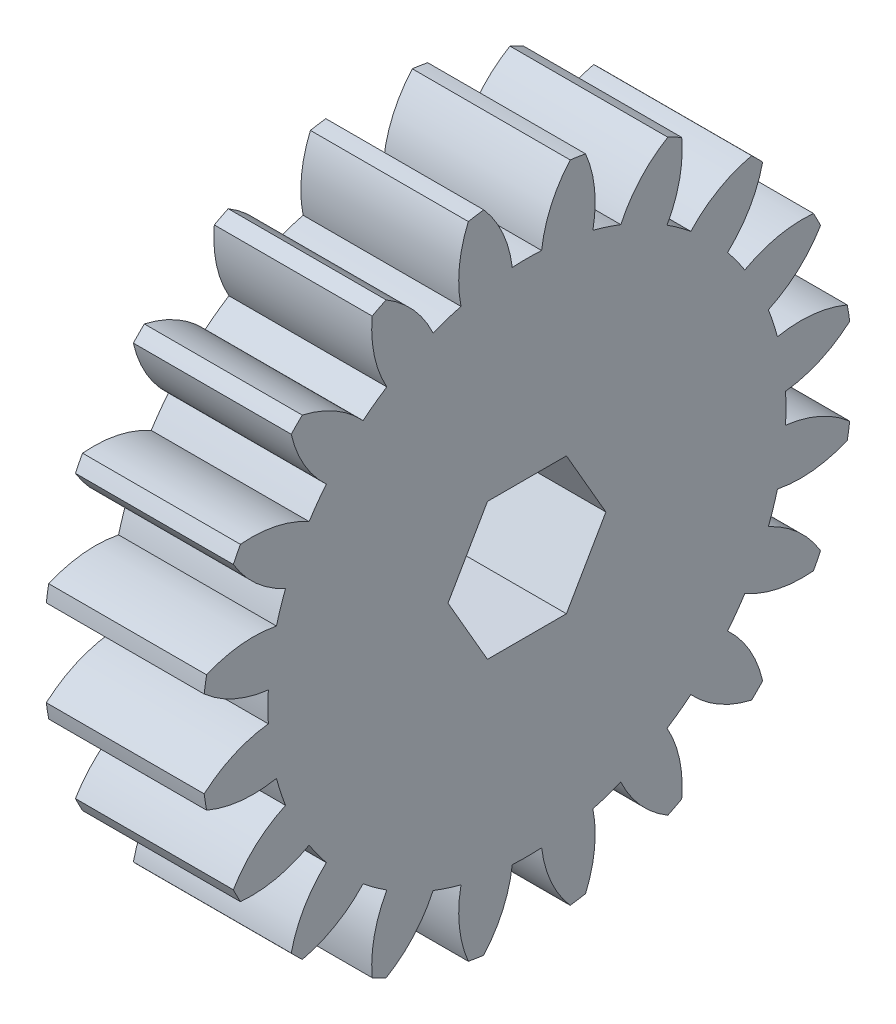
SolidWorks part; units mm, degrees
ref_plane "Plane1" through (0, 0, 0) normal (0, 0, 1) x (1, 0, 0)
ref_plane "Plane2" through (0, 0, 0) normal (0, 1, 0) x (1, 0, 0)
ref_plane "Plane3" through (0, 0, 0) normal (1, 0, 0) x (0, 0, -1)
sketch "HoldingSke" plane through (0, 0, 0) normal (0, 1, 0) x (1, 0, 0)
  line L0 (0, 0) -> (0.6265, -0.228)
  line L1 (-15, 0) -> (100, 0) construction
  line L2 (0, 0) -> (-2.1039, 2.3779)
  line L3 (0, 0) -> (-11.863, 4.5341)
  line L4 (0, 0) -> (8.1152, 2.9537)
  line L5 (0, 0) -> (-46.8476, -17.4728)
  line L6 (0, 0) -> (-9.9476, -6.7116)
  line L7 (-2.1039, 2.3779) -> (8.6586, 51.2059)
  line L8 (-76.2, 54.61) -> (-75.3, 54.61)
  line L9 (-71.009, 38.7566) -> (-53.1078, 45.2721)
  line L10 (-76.2, 71.12) -> (104.1128, 71.12)
  line L11 (0, 0) -> (-12, 0)
  line L12 (-76.2, 101.6) -> (-76.147, 101.6)
  line L13 (24.9733, 27.94) -> (52.9518, 28.4284)
  line L14 (24.9733, 27.94) -> (24.9743, 27.94)
  line L15 (24.9733, 27.94) -> (100.4006, 29.5858)
  line L16 (-63.627, -1.5) -> (-12.827, -1.5)
  circle A0 centre (0, 0) radius 2.5
  circle A1 centre (0, 0) radius 13.124
  circle A2 centre (0, 0) radius 37.5
  circle A3 centre (0, 0) radius 2.5
  dimension "MHD" = 26.248
  dimension "Hub_dia" = 75
  dimension "Bore" = 5
  dimension "MBD" = 5
  dimension "Num_teeth" = 20
  dimension "Pitch" = 0.6667
  dimension "Overall_len" = 50
  dimension "Show_teeth" = 20
  dimension "Thickness" = 12
  dimension "OAL" = 50.0001
  dimension "T_dim" = 0.9
  dimension "Ap" = 20
  dimension "H" = 19.05
  dimension "Pitch_radius" = 180.3128
  dimension "Width" = 12
  dimension "Backlash" = 0.053
  dimension "Addendum_fac" = 1
  dimension "Dedendum_fac" = 1.25
  dimension "Clearance_fac" = 0.25
  dimension "Dedendum_add" = 0.001
  dimension "Module" = 1.5
sketch "BasProSke" plane through (0, 0, 0) normal (0, 1, 0) x (1, 0, 0)
  line L0 (-10, 0) -> (60, 0) construction
  line L1 (0, 0) -> (0, 16.5)
  line L2 (0, 0) -> (8, 0)
  line L3 (8, 0) -> (8, 16.5)
  line L4 (8, 16.5) -> (0, 16.5)
  dimension "Thickness" = 8
  dimension "Diameter" = 33
revolve "Base-Revolve" add sketch "BasProSke" angle 360 about L0
sketch "TooCutSke" plane through (0, 0, 0) normal (1, 0, 0) x (0, 0, -1)
  line L1 (0, 0) -> (0, 107) construction
  line L2 (0, 0) -> (-1.2696, 14.9462) construction
  line L3 (0, 0) -> (-4.6808, 29.5532) construction
  line L4 (-1.2696, 14.9462) -> (-2.3404, 14.7766) construction
  arc A0 (0.7438, 13.1029) -> (-0.7438, 13.1029) centre (0, 0) ccw
  arc A1 (2.21, 16.377) -> (-2.21, 16.377) centre (0, 0) ccw
  circle A2 centre (0, 0) radius 15 construction
  circle A3 centre (0, 0) radius 14.0954 construction
  arc A4 (-0.7438, 13.1029) -> (-2.21, 16.377) centre (-6.7025, 12.3999) ccw
  arc A5 (2.21, 16.377) -> (0.7438, 13.1029) centre (6.7025, 12.3999) ccw
  dimension "Root_dia" = 26.248
  dimension "Overcut_dia" = 33.0508
  dimension "Pitch_dia" = 30
  dimension "Base_dia" = 28.1908
  dimension "Flank_rad" = 6
  dimension "Half_ang" = 9
  dimension "Half_CT" = 1.0841
extrude "ToothCut" cut sketch "TooCutSke" along normal through all
fillet "Breaks" [suppressed] radius 0.03
fillet "RootFillets" [suppressed] radius 0.376
pattern_circular "TeethCuts" count 20 every 18 about axis through (-10, 0, 0) along (1, 0, 0) of "ToothCut", "RootFillets", "Breaks"
sketch "HubNeaOneSke" plane through (0, 0, 0) normal (-1, 0, 0) x (0, 0, 1)
  circle A0 centre (0, 0) radius 13.124
  dimension "Diameter" = 26.248
extrude "HubNearOne" [suppressed] add sketch "HubNeaOneSke" along normal blind 42.0001
sketch "HubNeaBotSke" plane through (0, 0, 0) normal (-1, 0, 0) x (0, 0, 1)
  circle A0 centre (0, 0) radius 13.124
  dimension "Diameter" = 26.248
extrude "HubNearBoth" [suppressed] add sketch "HubNeaBotSke" along normal blind 21
ref_plane "FarPln" through (8, 0, 0) normal (1, 0, 0) x (0, 0, -1)
sketch "HubFarSke" plane through (8, 0, 0) normal (1, 0, 0) x (0, 0, -1)
  circle A0 centre (0, 0) radius 13.124
  dimension "Diameter" = 26.248
extrude "HubFar" [suppressed] add sketch "HubFarSke" along normal blind 21
sketch "BorSke" plane through (0, 0, 0) normal (1, 0, 0) x (0, 0, -1)
  circle A0 centre (0, 0) radius 2.5
  dimension "Diameter" = 5
extrude "Bore" cut sketch "BorSke" along normal mid plane 100.0001
sketch "KeySke" plane through (0, 0, 0) normal (1, 0, 0) x (0, 0, -1)
  line L0 (-1, 0) -> (-1, 3.4)
  line L1 (-1, 3.4) -> (1, 3.4)
  line L2 (1, 3.4) -> (1, 0)
  line L3 (0, 0) -> (0, 34) construction
  line L4 (-1, 0) -> (1, 0)
  dimension "Offset" = 3.4
  dimension "Width" = 2
extrude "Keyway" [suppressed] cut sketch "KeySke" along normal mid plane 100.0001
pattern_circular "Keyway2" [suppressed] count 2 every 90 about axis through (-10, 0, 0) along (1, 0, 0)
sketch "Sketch1" plane through (8, 0, 0) normal (1, 0, 0) x (0, 0, -1)
  line L1 (4, 0) -> (2, 3.4641)
  line L2 (2, 3.4641) -> (-2, 3.4641)
  line L3 (-2, 3.4641) -> (-4, 0)
  line L4 (-4, 0) -> (-2, -3.4641)
  line L5 (-2, -3.4641) -> (2, -3.4641)
  line L6 (2, -3.4641) -> (4, 0)
  circle A0 centre (0, 0) radius 3.4641 construction
  circle A1 centre (0, 0) radius 4 construction
  dimension "D1" = 8
extrude "Cut-Extrude1" cut sketch "Sketch1" against normal through all
ref_plane "Plane4" through (8, 16.2303, -2.9711) normal (1, 0, 0) x (0, 0, -1)
sketch "Sketch2" plane through (8, 16.2303, -2.9711) normal (1, 0, 0) x (0, 0, -1)
  line L0 (-6.9711, -16.2303) -> (-4.9711, -19.6944) construction
  line L1 (-4.9711, -19.6944) -> (-0.9711, -19.6944) construction
  line L2 (-0.9711, -19.6944) -> (1.0289, -16.2303) construction
  line L3 (1.0289, -16.2303) -> (-0.9711, -12.7662) construction
  line L4 (-0.9711, -12.7662) -> (-4.9711, -12.7662) construction
  line L5 (-4.9711, -12.7662) -> (-6.9711, -16.2303) construction
  line L6 (-4.9711, -12.7662) -> (-6.9711, -16.2303)
  line L7 (-0.9711, -12.7662) -> (-4.9711, -12.7662)
  line L8 (1.0289, -16.2303) -> (-0.9711, -12.7662)
  line L9 (-0.9711, -19.6944) -> (1.0289, -16.2303)
  line L10 (-4.9711, -19.6944) -> (-0.9711, -19.6944)
  line L11 (-6.9711, -16.2303) -> (-4.9711, -19.6944)
  circle A0 centre (-2.9711, -16.2303) radius 7.5
  dimension "D1" = 15
extrude "Boss-Extrude1" [suppressed] add sketch "Sketch2" along normal blind 2.5
sketch "Sketch3" plane through (0, 0, 0) normal (-1, 0, 0) x (0, 0, 1)
  line L0 (2, 3.4641) -> (4, 0) construction
  line L1 (-2, 3.4641) -> (2, 3.4641) construction
  line L2 (-4, 0) -> (-2, 3.4641) construction
  line L3 (-2, -3.4641) -> (-4, 0) construction
  line L4 (2, -3.4641) -> (-2, -3.4641) construction
  line L5 (4, 0) -> (2, -3.4641) construction
  line L6 (4, 0) -> (2, -3.4641)
  line L7 (2, -3.4641) -> (-2, -3.4641)
  line L8 (-2, -3.4641) -> (-4, 0)
  line L9 (-4, 0) -> (-2, 3.4641)
  line L10 (-2, 3.4641) -> (2, 3.4641)
  line L11 (2, 3.4641) -> (4, 0)
  circle A0 centre (0, 0) radius 7.5
  dimension "D1" = 15
extrude "Boss-Extrude2" [suppressed] add sketch "Sketch3" along normal blind 2.5
equation "' \"Module@HoldingSke\" = 6.35"
equation "' \"Num_teeth@HoldingSke\" = 12"
equation "' \"Ap@HoldingSke\" =  20"
equation "' \"Ap@HoldingSke\" = 20"
equation "' \"Width@HoldingSke\" = 0.5 * 25.4"
equation "' \"Hub_dia@HoldingSke\"= 1 * 25.4"
equation "' \"Hub_dia@HoldingSke\" = 1 * 25.4"
equation "' \"Overall_len@HoldingSke\" = 1.0 * 25.4"
equation "' \"Bore@HoldingSke\" = 0.75 * 25.4"
equation "' \"T_dim@HoldingSke\" = 0.1 * 25.4"
equation "' \"Width@KeySke\" = 0.25 * 25.4"
equation "' \"Show_teeth@HoldingSke\" = 13"
equation "' \"Backlash@HoldingSke\" = 0.009 * 25.4"
equation "' \"Addendum_fac@HoldingSke\" = 1.0"
equation "' \"Dedendum_fac@HoldingSke\" = 1.25"
equation "' \"Dedendum_add@HoldingSke\" = 0.00005 * 25.4"
equation "' \"Clearance_fac@HoldingSke\" = 0.25"
equation "\"Pitch@HoldingSke\" = 1 / \"Module@HoldingSke\""
equation "\"Overcut_dia@TooCutSke\" = (\"Num_teeth@HoldingSke\" + 2 * \"Addendum_fac@HoldingSke\") / \"Pitch@HoldingSke\" + 0.002 * 25.4"
equation "\"Pitch_dia@TooCutSke\" = \"Num_teeth@HoldingSke\" / \"Pitch@HoldingSke\""
equation "\"Base_dia@TooCutSke\" = \"Num_teeth@HoldingSke\" / \"Pitch@HoldingSke\" * cos((\"Ap@HoldingSke\"  * 3.14159265 / 180))"
equation "\"Root_dia@TooCutSke\" = (\"Num_teeth@HoldingSke\" + 2) / \"Pitch@HoldingSke\" - 2 * (\"Addendum_fac@HoldingSke\" + \"Dedendum_fac@HoldingSke\") / \"Pitch@HoldingSke\" - \"Dedendum_add@HoldingSke\" * 2"
equation "\"Half_ang@TooCutSke\" = 180 / \"Num_teeth@HoldingSke\""
equation "\"Half_CT@TooCutSke\" = \"Num_teeth@HoldingSke\" / \"Pitch@HoldingSke\" * sin((3.14159265 / 2 / \"Num_teeth@HoldingSke\")) / 2 - 7 * \"Backlash@HoldingSke\" / 4"
equation "\"Flank_rad@TooCutSke\" = \"Num_teeth@HoldingSke\" / \"Pitch@HoldingSke\" / 5"
equation "\"Radius@RootFillets\" = \"Clearance_fac@HoldingSke\" / \"Pitch@HoldingSke\" + \"Dedendum_add@HoldingSke\""
equation "\"Break_rad@Breaks\" = 0.02 / \"Pitch@HoldingSke\""
equation "\"Thickness@HoldingSke\" = \"Width@HoldingSke\""
equation "\"OAL@HoldingSke\" = \"Thickness@HoldingSke\""
equation "\"MHD@HoldingSke\" = (\"Num_teeth@HoldingSke\" + 2) / \"Pitch@HoldingSke\" - 2 * (\"Addendum_fac@HoldingSke\" + \"Dedendum_fac@HoldingSke\")  / \"Pitch@HoldingSke\" - \"Dedendum_add@HoldingSke\" * 2"
equation "\"MBD@HoldingSke\" = (\"Num_teeth@HoldingSke\" + 2) / \"Pitch@HoldingSke\" - 2 * (\"Addendum_fac@HoldingSke\" + \"Dedendum_fac@HoldingSke\")  / \"Pitch@HoldingSke\" - \"Dedendum_add@HoldingSke\" * 2 - 0.002 * 25.4"
equation "\"MHD@HoldingSke\" = ((sgn( \"MHD@HoldingSke\" - \"Hub_dia@HoldingSke\" )-1)*( \"MHD@HoldingSke\" - \"Hub_dia@HoldingSke\" ))/-2+ \"Hub_dia@HoldingSke\""
equation "\"MBD@HoldingSke\" = ((sgn( \"MBD@HoldingSke\" - \"Bore@HoldingSke\" )-1)*( \"MBD@HoldingSke\" - \"Bore@HoldingSke\" ))/-2+ \"Bore@HoldingSke\""
equation "\"OAL@HoldingSke\" = ((sgn( \"OAL@HoldingSke\" - \"Overall_len@HoldingSke\" )+1)*( \"OAL@HoldingSke\" - \"Overall_len@HoldingSke\" ))/2 + \"Overall_len@HoldingSke\" + 0.000002 * 25.4"
equation "\"Num_teeth@TeethCuts\" = int( \"Show_teeth@HoldingSke\" ) + 1"
equation "\"Num_teeth@TeethCuts\" = ((sgn( \"Num_teeth@TeethCuts\" - \"Num_teeth@HoldingSke\" )-1)*( \"Num_teeth@TeethCuts\" - \"Num_teeth@HoldingSke\" ))/-2+ \"Num_teeth@HoldingSke\""
equation "\"Num_teeth@TeethCuts\" = ((sgn( \"Num_teeth@TeethCuts\" - 2.0)+1)*( \"Num_teeth@TeethCuts\" - 2.0))/2 +2.0"
equation "\"Angle@TeethCuts\" = 360.0 / \"Num_teeth@HoldingSke\""
equation "\"Diameter@BasProSke\" = (\"Num_teeth@HoldingSke\" + 2 * \"Addendum_fac@HoldingSke\") / \"Pitch@HoldingSke\""
equation "\"Thickness@BasProSke\"=8"
equation "' \"Fillet_rad@BasProSke\" =  \"Thickness@HoldingSke\" * 0.05"
equation "' \"Fillet_rad@BasProSke\" = \"Thickness@HoldingSke\" * 0.05"
equation "\"MHD@HoldingSke\" = ((sgn( \"MHD@HoldingSke\" - \"Root_dia@TooCutSke\" )-1)*( \"MHD@HoldingSke\" - \"Root_dia@TooCutSke\" ))/-2+ \"Root_dia@TooCutSke\""
equation "\"Diameter@HubNeaOneSke\" = \"MHD@HoldingSke\""
equation "\"Length@HubNearOne\" = \"OAL@HoldingSke\" - \"Thickness@BasProSke\""
equation "\"Diameter@HubNeaBotSke\" = \"MHD@HoldingSke\""
equation "\"Length@HubNearBoth\" = ( \"OAL@HoldingSke\" - \"Thickness@BasProSke\" ) / 2.0"
equation "\"Thickness@FarPln\" = \"Thickness@BasProSke\""
equation "\"Diameter@HubFarSke\" = \"MHD@HoldingSke\""
equation "\"Length@HubFar\" = ( \"OAL@HoldingSke\" - \"Thickness@BasProSke\" ) / 2.0"
equation "\"Diameter@BorSke\" = \"MBD@HoldingSke\""
equation "\"D1@Bore\" = \"OAL@HoldingSke\" * 2.0"
equation "\"D1@Keyway\" = \"OAL@HoldingSke\" * 2.0"
equation "\"Offset@KeySke\" = \"T_dim@HoldingSke\" + \"MBD@HoldingSke\" / 2.0"
